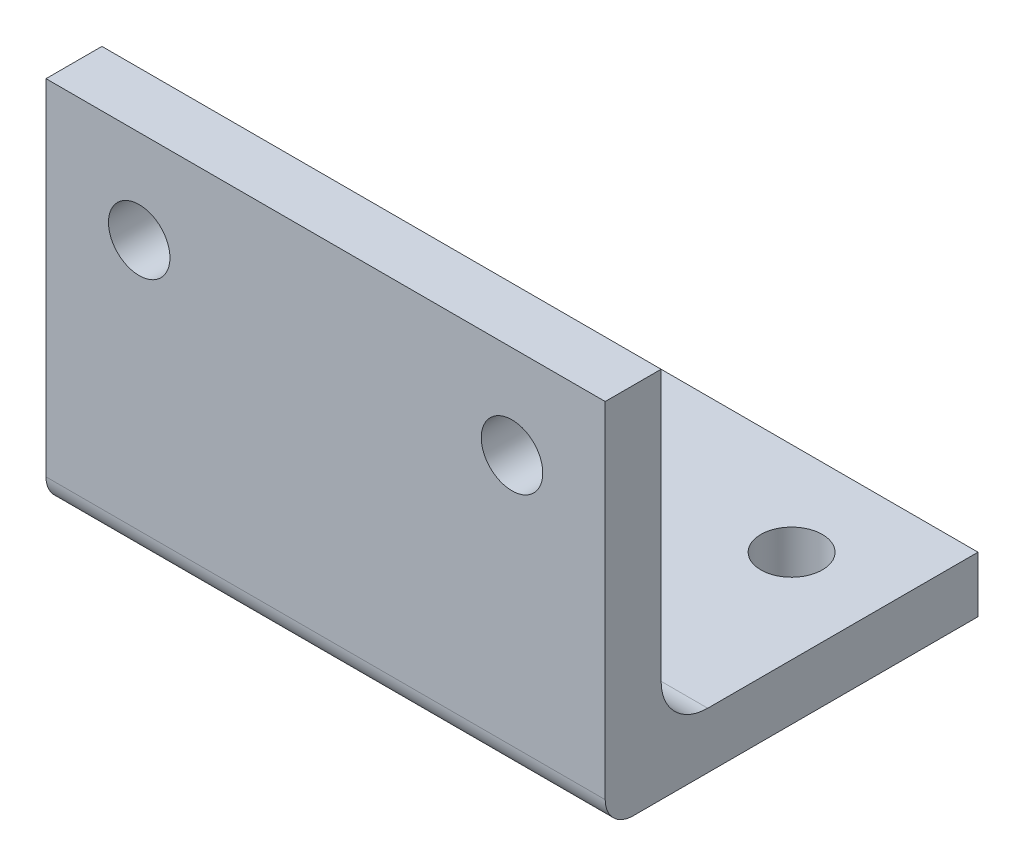
SolidWorks part; units mm, degrees
ref_plane "前基準面" through (0, 0, 0) normal (0, 0, 1) x (1, 0, 0)
ref_plane "上基準面" through (0, 0, 0) normal (0, 1, 0) x (1, 0, 0)
ref_plane "右基準面" through (0, 0, 0) normal (1, 0, 0) x (0, 0, -1)
sketch "草圖1" plane through (0, 0, 0) normal (1, 0, 0) x (0, 0, -1)
  line L0 (0, 0) -> (40, 0)
  line L1 (40, 0) -> (40, 6)
  line L2 (40, 6) -> (6, 6)
  line L3 (6, 6) -> (6, 40)
  line L4 (6, 40) -> (0, 40)
  line L5 (0, 40) -> (0, 0)
extrude "填料-伸長1" add sketch "草圖1" along normal blind 60
sketch "草圖2" plane through (0, 0, 0) normal (0, 1, 0) x (1, 0, 0)
  circle A0 centre (10, 30) radius 3.3
  circle A1 centre (50, 30) radius 3.3
extrude "除料-伸長1" cut sketch "草圖2" along normal through all
sketch "草圖3" plane through (0, 0, 0) normal (0, 0, 1) x (1, 0, 0)
  circle A0 centre (10, 30) radius 3.3
  circle A1 centre (50, 30) radius 3.3
extrude "除料-伸長2" cut sketch "草圖3" against normal through all
fillet "圓角1" radius 5 1 edges at (30, 6, -6)
fillet "圓角2" radius 3 1 edges at (30, 0, 0)
